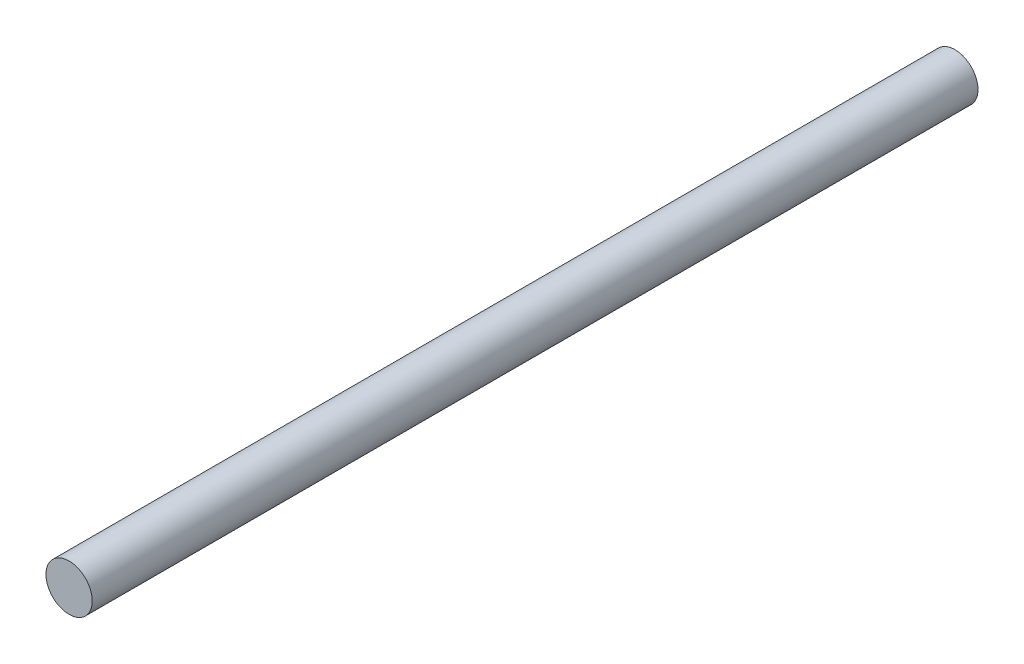
SolidWorks part; units mm, degrees
material "СТ3КП"
ref_plane "Спереди" through (0, 0, 0) normal (0, 0, 1) x (1, 0, 0)
ref_plane "Сверху" through (0, 0, 0) normal (0, 1, 0) x (1, 0, 0)
ref_plane "Справа" through (0, 0, 0) normal (1, 0, 0) x (0, 0, -1)
sketch "Эскиз1" plane through (0, 0, 0) normal (0, 0, 1) x (1, 0, 0)
  circle A0 centre (0, 0) radius 9 construction
  circle A1 centre (0, 0) radius 9
extrude "Бобышка-Вытянуть1" add sketch "Эскиз1" along normal up to surface (172.3 mm away)
mirror "Зеркальное отражение1" about plane through (0, 0, 0) normal (0, 0, 1) of bodies 103
